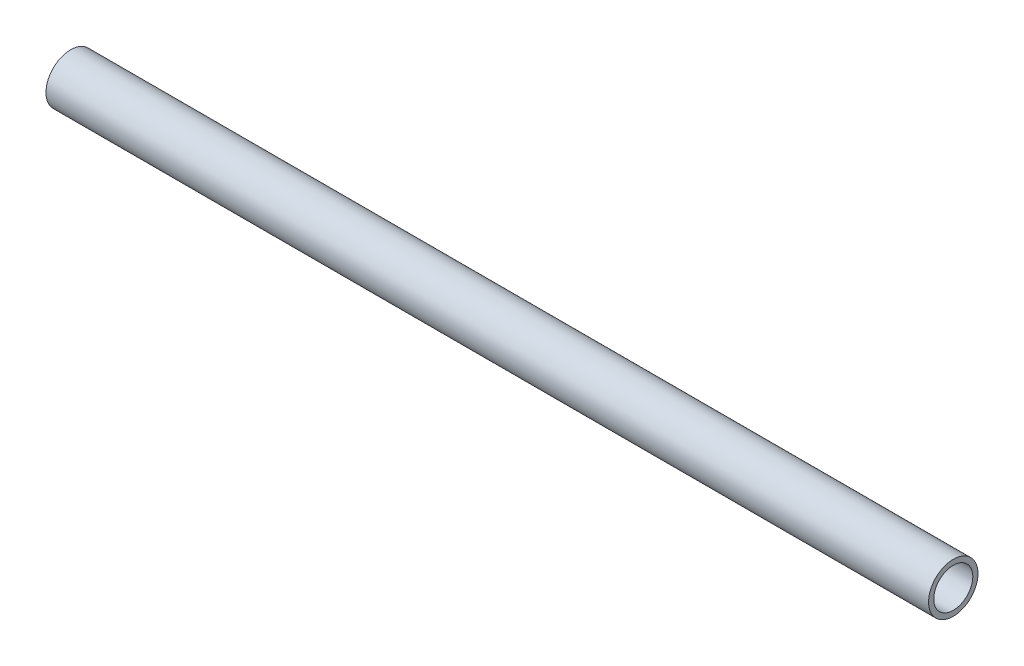
SolidWorks part; units mm, degrees
ref_plane "Front Plane" through (0, 0, 0) normal (0, 0, 1) x (1, 0, 0)
ref_plane "Top Plane" through (0, 0, 0) normal (0, 1, 0) x (1, 0, 0)
ref_plane "Right Plane" through (0, 0, 0) normal (1, 0, 0) x (0, 0, -1)
sketch "Sketch1" plane through (0, 0, 0) normal (1, 0, 0) x (0, 0, -1)
  circle A0 centre (0, 0) radius 9.525
  circle A1 centre (0, 0) radius 7.525
  dimension "D1" = 19.05
  dimension "D2" = 2
extrude "Boss-Extrude1" add sketch "Sketch1" along normal blind 340
